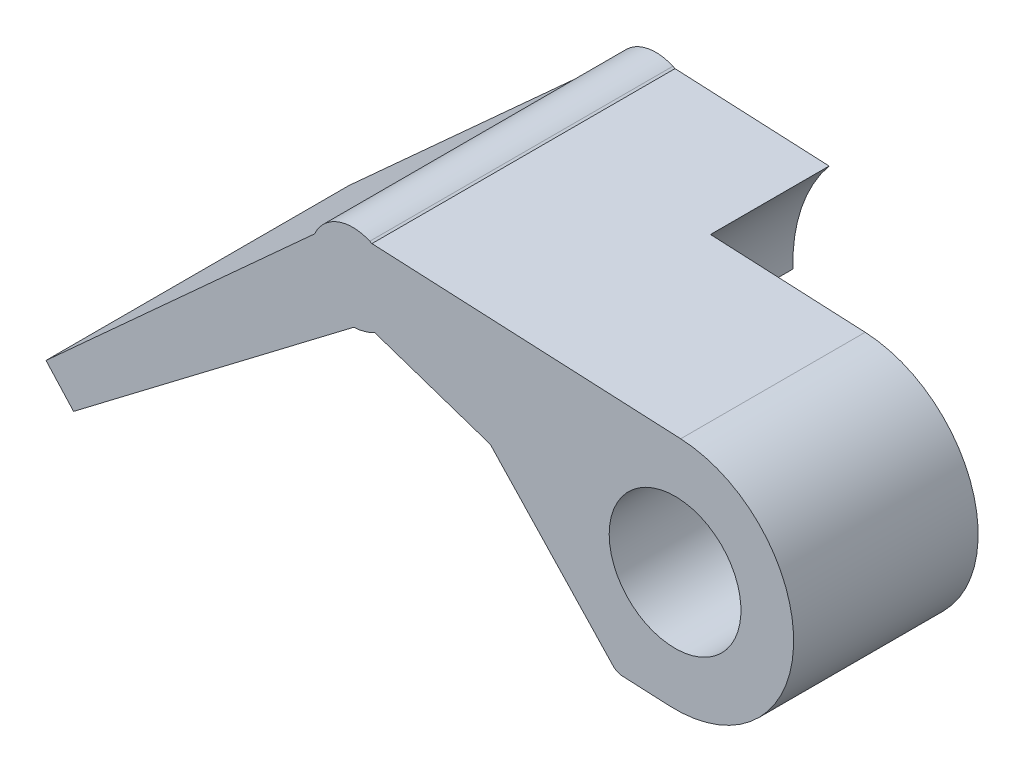
SolidWorks part; units mm, degrees
ref_plane "Front Plane" through (0, 0, 0) normal (0, 0, 1) x (1, 0, 0)
ref_plane "Top Plane" through (0, 0, 0) normal (0, 1, 0) x (1, 0, 0)
ref_plane "Right Plane" through (0, 0, 0) normal (1, 0, 0) x (0, 0, -1)
sketch "Sketch1" plane through (0, 0, 0) normal (0, 0, 1) x (1, 0, 0)
  line L0 (-26.2781, -11.3478) -> (-28.3722, -9.0438)
  line L1 (-28.3722, -9.0438) -> (-7.9902, 9.4622)
  line L2 (-3.8009, 11.0746) -> (-3.6375, 11.002)
  line L3 (-3.6375, 11.002) -> (19.794, 9.8897)
  line L4 (18.9406, -8.0881) -> (15.3487, -7.9165)
  line L5 (14.6682, -7.603) -> (5.3501, 2.2966)
  line L6 (5.3501, 2.2966) -> (-3.4192, 5.2559)
  line L7 (-5.0141, 4.8134) -> (-26.2781, -11.3478)
  arc A0 (-7.9902, 9.4622) -> (-3.8009, 11.0746) centre (-5.0894, 8.1738) cw
  arc A1 (19.794, 9.8897) -> (18.9406, -8.0881) centre (19.3673, 0.9008) cw
  arc A2 (15.3487, -7.9165) -> (14.6682, -7.603) centre (15.3965, -6.9175) cw
  arc A3 (-3.4192, 5.2559) -> (-5.0141, 4.8134) centre (-5.1897, 8.5415) cw
extrude "Boss-Extrude1" add sketch "Sketch1" along normal blind 23
ref_plane "Plane1" through (30, 0, 0) normal (1, 0, 0) x (0, 0, -1)
sketch "Sketch4" plane through (0, 0, 0) normal (0, 0, -1) x (-1, 0, 0)
  line L0 (-19.794, 9.8897) -> (-18.9406, -8.0881) construction
  line L1 (-28.3562, 0.4741) -> (-9.3065, 1.3784) construction
  arc A0 (-19.794, 9.8897) -> (-18.9406, -8.0881) centre (-19.3673, 0.9008) ccw construction
  circle A1 centre (-19.3673, 0.9008) radius 5
extrude "Cut-Extrude3" cut sketch "Sketch4" against normal blind 28
sketch "Sketch5" plane through (0, 0, 0) normal (0, 0, -1) x (-1, 0, 0)
  line L4 (-8.2808, 10.7151) -> (-20.3419, 10.1425)
  line L5 (-14.6361, -7.6142) -> (-5.3181, 2.2854)
  line L6 (-18.9043, -8.0991) -> (-15.3167, -7.9277)
  arc A3 (-15.3167, -7.9277) -> (-14.6361, -7.6142) centre (-15.3644, -6.9287) ccw
  arc A4 (-5.3181, 2.2854) -> (-8.2808, 10.7151) centre (-17.5517, 2.7212) ccw
  arc A5 (-20.3419, 10.1425) -> (-18.9043, -8.0991) centre (-19.6321, 1.021) ccw
extrude "Cut-Extrude4" cut sketch "Sketch5" against normal blind 9
